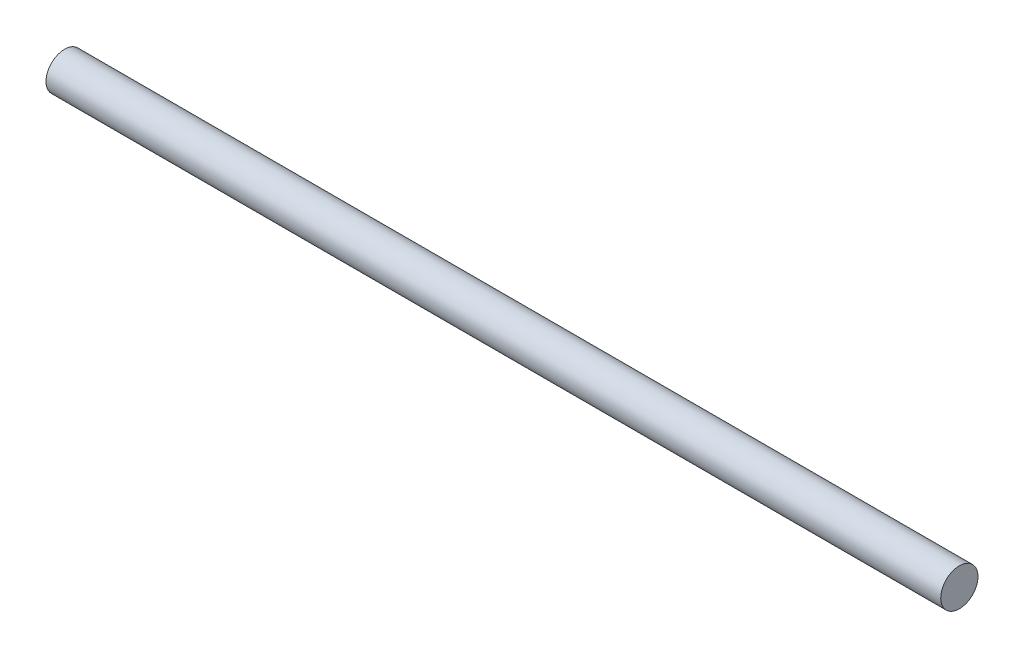
SolidWorks part; units mm, degrees
ref_plane "Plan de face" through (0, 0, 0) normal (0, 0, 1) x (1, 0, 0)
ref_plane "Plan de dessus" through (0, 0, 0) normal (0, 1, 0) x (1, 0, 0)
ref_plane "Plan de droite" through (0, 0, 0) normal (1, 0, 0) x (0, 0, -1)
sketch "Esquisse1" plane through (0, 0, 0) normal (0, 0, 1) x (1, 0, 0)
  line L1 (0, 0) -> (-240, 0)
  line L2 (0, 0) -> (0, 5)
  line L3 (0, 5) -> (-240, 5)
  line L4 (-240, 0) -> (-240, 5)
  dimension "D1" = 5
  dimension "D2" = 240
revolve "Révolution1" add sketch "Esquisse1" angle 360 about L3
